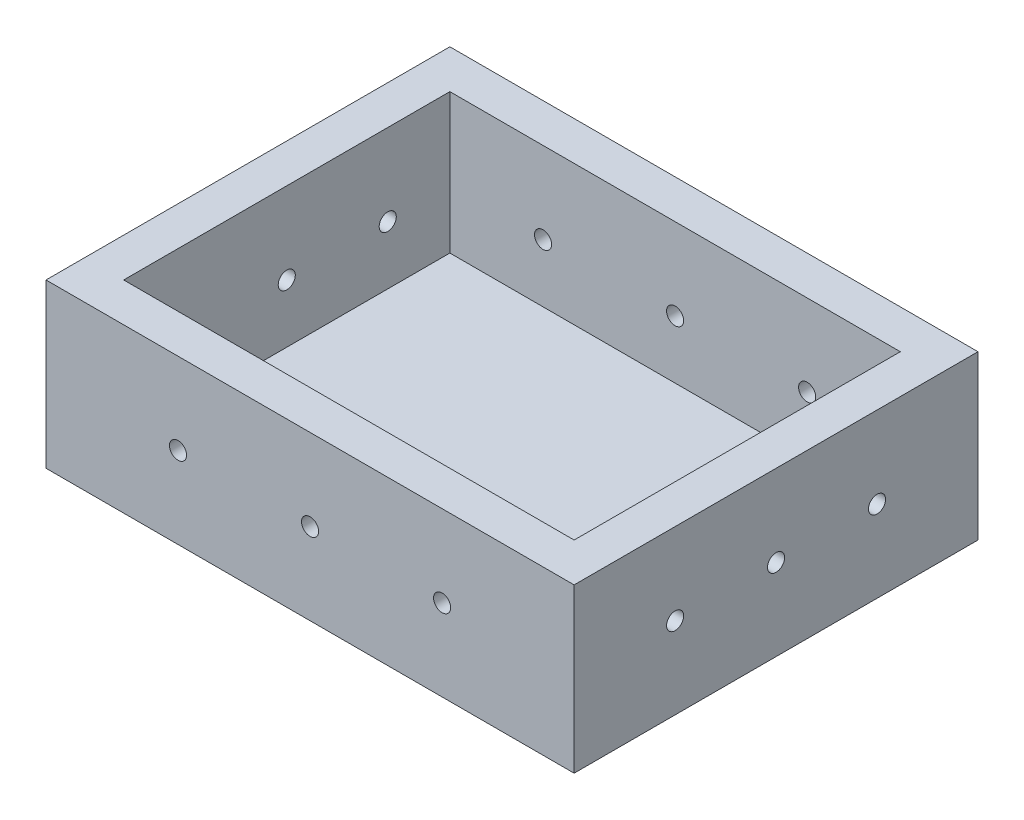
SolidWorks part; units mm, degrees
ref_plane "前视基准面" through (0, 0, 0) normal (0, 0, 1) x (1, 0, 0)
ref_plane "上视基准面" through (0, 0, 0) normal (0, 1, 0) x (1, 0, 0)
ref_plane "右视基准面" through (0, 0, 0) normal (1, 0, 0) x (0, 0, -1)
sketch "草图1" plane through (0, 0, 0) normal (0, 1, 0) x (1, 0, 0)
  line L1 (-68, 52) -> (68, 52)
  line L2 (-68, 52) -> (-68, -52)
  line L3 (-68, -52) -> (68, -52)
  line L4 (68, 52) -> (68, -52)
  line L5 (-68, 52) -> (68, -52) construction
  line L6 (-68, -52) -> (68, 52) construction
  point P0 (0, 0)
  dimension "D1" = 136
  dimension "D2" = 104
extrude "凸台-拉伸1" add sketch "草图1" along normal blind 42
sketch "草图2" plane through (0, 42, 0) normal (0, 1, 0) x (1, 0, 0)
  line L1 (-58, 42) -> (58, 42)
  line L2 (-58, 42) -> (-58, -42)
  line L3 (-58, -42) -> (58, -42)
  line L4 (58, 42) -> (58, -42)
  line L5 (-58, 42) -> (58, -42) construction
  line L6 (-58, -42) -> (58, 42) construction
  point P0 (0, 0)
  dimension "D1" = 116
  dimension "D2" = 84
extrude "切除-拉伸1" cut sketch "草图2" against normal blind 36
sketch "草图6" plane through (-68, 0, 0) normal (-1, 0, 0) x (0, 0, 1)
  line L0 (-52, 21) -> (52, 21) construction
  line L1 (-52, 42) -> (-52, 0) construction
  line L2 (52, 42) -> (52, 0) construction
  line L3 (0, 42) -> (0, 0) construction
  line L4 (-52, 42) -> (52, 42) construction
  circle A0 centre (-26, 21) radius 2.2
  circle A1 centre (26, 21) radius 2.2
  circle A2 centre (0, 21) radius 2.2
  dimension "D1" = 4.4
  dimension "D2" = 4.4
  dimension "D5" = 4.4
  dimension "D3" = 26
  dimension "D4" = 26
extrude "切除-拉伸5" cut sketch "草图6" against normal blind 136
sketch "草图7" plane through (0, 0, -52) normal (0, 0, -1) x (-1, 0, 0)
  line L0 (-68, 21) -> (68, 21) construction
  line L1 (-68, 42) -> (-68, 0) construction
  line L2 (68, 42) -> (68, 0) construction
  line L3 (0, 42) -> (0, 0) construction
  line L4 (-68, 42) -> (68, 42) construction
  circle A0 centre (-34, 21) radius 2.2
  circle A1 centre (34, 21) radius 2.2
  circle A2 centre (0, 21) radius 2.2
  dimension "D1" = 4.4
  dimension "D2" = 4.4
  dimension "D3" = 4.4
  dimension "D4" = 34
  dimension "D5" = 34
extrude "切除-拉伸6" cut sketch "草图7" against normal blind 104
